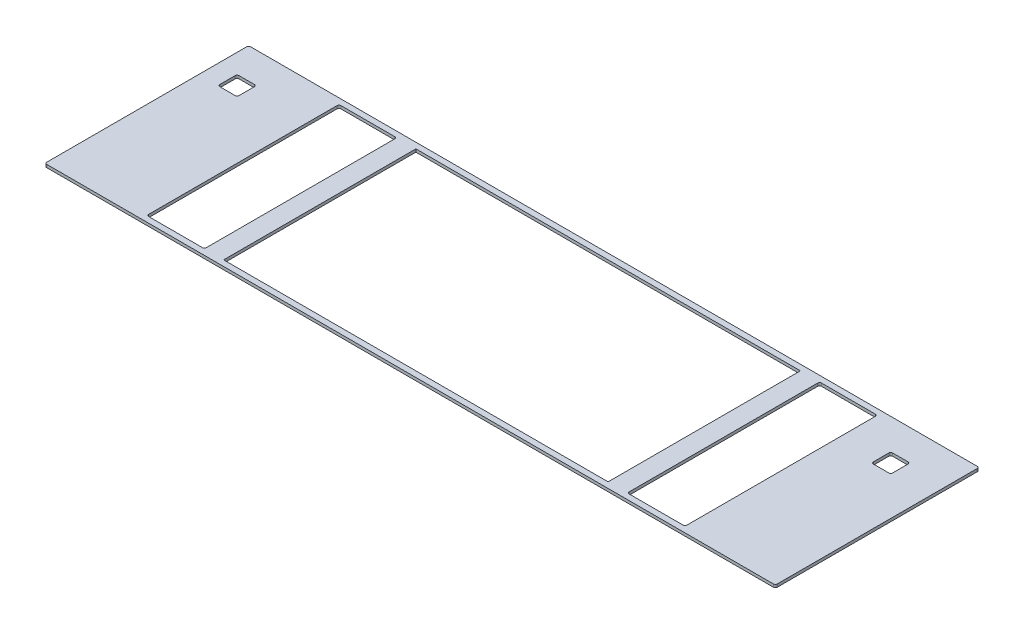
SolidWorks part; units mm, degrees
ref_plane "前视基准面" through (0, 0, 0) normal (0, 0, 1) x (1, 0, 0)
ref_plane "上视基准面" through (0, 0, 0) normal (0, 1, 0) x (1, 0, 0)
ref_plane "右视基准面" through (0, 0, 0) normal (1, 0, 0) x (0, 0, -1)
sketch "草图1" plane through (0, 0, 0) normal (0, 1, 0) x (1, 0, 0)
  line L1 (2, 0) -> (758, 0)
  line L2 (0, 2) -> (0, 210)
  line L3 (2, 212) -> (758, 212)
  line L4 (760, 2) -> (760, 210)
  line L5 (580, 6) -> (180, 6)
  line L6 (580, 6) -> (580, 206)
  line L7 (580, 206) -> (180, 206)
  line L8 (180, 6) -> (180, 206)
  line L9 (658, 6) -> (602, 6)
  line L10 (660, 8) -> (660, 204)
  line L11 (658, 206) -> (602, 206)
  line L12 (600, 8) -> (600, 204)
  line L13 (158, 6) -> (102, 6)
  line L14 (160, 8) -> (160, 204)
  line L15 (158, 206) -> (102, 206)
  line L16 (100, 8) -> (100, 204)
  line L17 (38, 160) -> (22, 160)
  line L18 (40, 162) -> (40, 178)
  line L19 (38, 180) -> (22, 180)
  line L20 (20, 162) -> (20, 178)
  line L21 (718, 160) -> (702, 160)
  line L22 (720, 162) -> (720, 178)
  line L23 (718, 180) -> (702, 180)
  line L24 (700, 162) -> (700, 178)
  arc A0 (758, 212) -> (760, 210) centre (758, 210) cw
  arc A1 (758, 0) -> (760, 2) centre (758, 2) ccw
  arc A2 (2, 0) -> (0, 2) centre (2, 2) cw
  arc A3 (2, 212) -> (0, 210) centre (2, 210) ccw
  arc A4 (720, 162) -> (718, 160) centre (718, 162) cw
  arc A5 (718, 180) -> (720, 178) centre (718, 178) cw
  arc A6 (702, 180) -> (700, 178) centre (702, 178) ccw
  arc A7 (700, 162) -> (702, 160) centre (702, 162) ccw
  arc A8 (22, 180) -> (20, 178) centre (22, 178) ccw
  arc A9 (38, 180) -> (40, 178) centre (38, 178) cw
  arc A10 (40, 162) -> (38, 160) centre (38, 162) cw
  arc A11 (20, 162) -> (22, 160) centre (22, 162) ccw
  arc A12 (600, 8) -> (602, 6) centre (602, 8) ccw
  arc A13 (602, 206) -> (600, 204) centre (602, 204) ccw
  arc A14 (658, 206) -> (660, 204) centre (658, 204) cw
  arc A15 (660, 8) -> (658, 6) centre (658, 8) cw
  arc A16 (158, 6) -> (160, 8) centre (158, 8) ccw
  arc A17 (158, 206) -> (160, 204) centre (158, 204) cw
  arc A18 (100, 204) -> (102, 206) centre (102, 204) cw
  arc A19 (100, 8) -> (102, 6) centre (102, 8) ccw
  point P9 (760, 0)
  point P12 (0, 0)
  point P15 (0, 212)
  point P38 (720, 160)
  point P41 (720, 180)
  point P46 (700, 160)
  point P51 (40, 180)
  point P54 (40, 160)
  point P57 (20, 160)
  point P60 (600, 6)
  point P65 (660, 206)
  point P68 (660, 6)
  point P71 (160, 6)
  point P74 (160, 206)
  point P79 (100, 6)
  dimension "D3" = 2
  dimension "D4" = 200
  dimension "D7" = 60
  dimension "D10" = 20
  dimension "D13" = 20
  dimension "D20" = 20
  dimension "D23" = 40
  dimension "D26" = 2
  dimension "D24" = 2
  dimension "D25" = 2
  dimension "D27" = 2
  dimension "D1" = 212
  dimension "D2" = 760
  dimension "D5" = 6
  dimension "D6" = 20
  dimension "D8" = 200
  dimension "D9" = 6
  dimension "D11" = 60
  dimension "D12" = 20
  dimension "D14" = 20
  dimension "D15" = 160
  dimension "D16" = 400
  dimension "D17" = 200
  dimension "D18" = 180
  dimension "D19" = 6
  dimension "D21" = 20
  dimension "D22" = 160
extrude "凸台-拉伸1" add sketch "草图1" against normal blind 3
